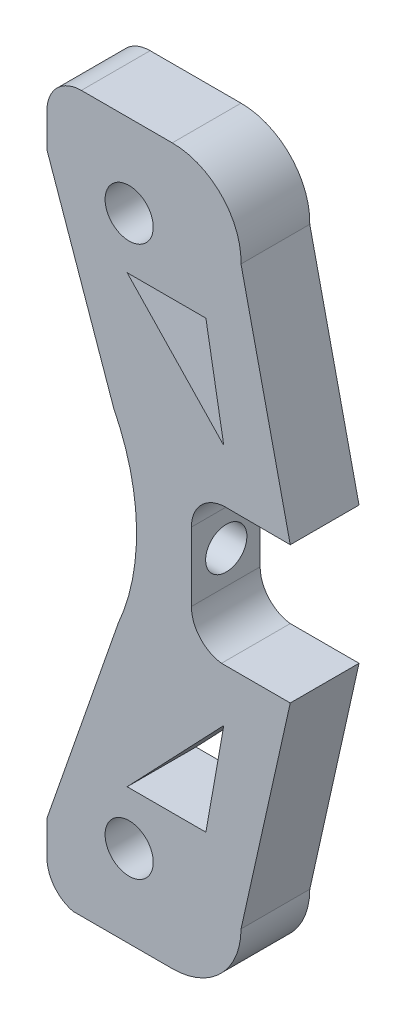
SolidWorks part; units mm, degrees
ref_plane "Plano frontal" through (0, 0, 0) normal (0, 0, 1) x (1, 0, 0)
ref_plane "Plano superior" through (0, 0, 0) normal (0, 1, 0) x (1, 0, 0)
ref_plane "Plano direito" through (0, 0, 0) normal (1, 0, 0) x (0, 0, -1)
sketch "Esboço1" plane through (0, 0, 0) normal (0, 0, 1) x (1, 0, 0)
  line L0 (16.4778, 11.1725) -> (9.3164, 42.9498)
  line L1 (-0.6802, 53.2113) -> (-13.9002, 53.2113)
  line L2 (-18.9002, 48.2113) -> (-18.9002, 43.2113)
  line L3 (16.4778, -8.7498) -> (9.3198, -40.7887)
  line L4 (-18.9002, 43.2113) -> (-9.1995, 15.5416)
  line L5 (-0.6802, -50.7887) -> (-13.9002, -50.7887)
  line L6 (-18.9002, -45.9465) -> (-18.9002, -40.9465)
  line L7 (-18.9002, -40.9465) -> (-8.553, -11.2568)
  line L8 (7.0998, 11.2113) -> (16.4778, 11.1725)
  line L9 (2.0998, 6.2093) -> (2.0998, -3.7887)
  line L10 (6.4778, -8.7498) -> (16.4778, -8.7498)
  line L11 (-15.1466, -50.7887) -> (-13.9002, -50.7887)
  line L12 (-7.2404, 33.5813) -> (4.2096, 33.5813)
  line L13 (4.2096, 33.5813) -> (6.8088, 18.8454)
  line L14 (6.8088, 18.8454) -> (-7.2404, 33.5813)
  line L15 (4.2096, -31.1587) -> (6.8088, -16.4227)
  line L16 (-7.2404, -31.1587) -> (4.2096, -31.1587)
  line L17 (6.8088, -16.4227) -> (-7.2404, -31.1587)
  arc A0 (9.3164, 42.9498) -> (-0.6802, 53.2113) centre (-0.6802, 43.2113) ccw
  arc A1 (-13.9002, 53.2113) -> (-18.9002, 48.2113) centre (-13.9002, 48.2113) ccw
  arc A2 (-8.553, -11.2568) -> (-9.1995, 15.5416) centre (-37.3374, 1.4559) ccw
  arc A3 (-18.9002, -45.9465) -> (-15.1466, -50.7887) centre (-13.9002, -45.9465) ccw
  arc A4 (-0.6802, -50.7887) -> (9.3198, -40.7887) centre (-0.6802, -40.7887) ccw
  arc A6 (7.0998, 11.2113) -> (2.0998, 6.2093) centre (7.1019, 6.2093) ccw
  arc A7 (2.0998, -3.7887) -> (6.4778, -8.7498) centre (7.0998, -3.7887) ccw
  circle A9 centre (-6.9502, 41.2113) radius 3.5
  circle A10 centre (-6.9502, -38.7887) radius 3.5
  dimension "D5" = 7
  dimension "D13" = 12
  dimension "D1" = 13.22
  dimension "D2" = 5
  dimension "D3" = 5
  dimension "D4" = 11.45
  dimension "D6" = 33.63
  dimension "D7" = 20.36
  dimension "D8" = 7.63
  dimension "D9" = 20.36
  dimension "D10" = 33.63
  dimension "D11" = 7.63
  dimension "D12" = 80
  dimension "D14" = 11.95
extrude "Ressalto-extrusão1" add sketch "Esboço1" along normal blind 10
sketch "Esboço2" plane through (2.0998, 0, 0) normal (1, 0, 0) x (0, 0, -1)
  circle A0 centre (-4.9283, 1.0213) radius 3
extrude "Corte-extrusão1" cut sketch "Esboço2" against normal blind 10
